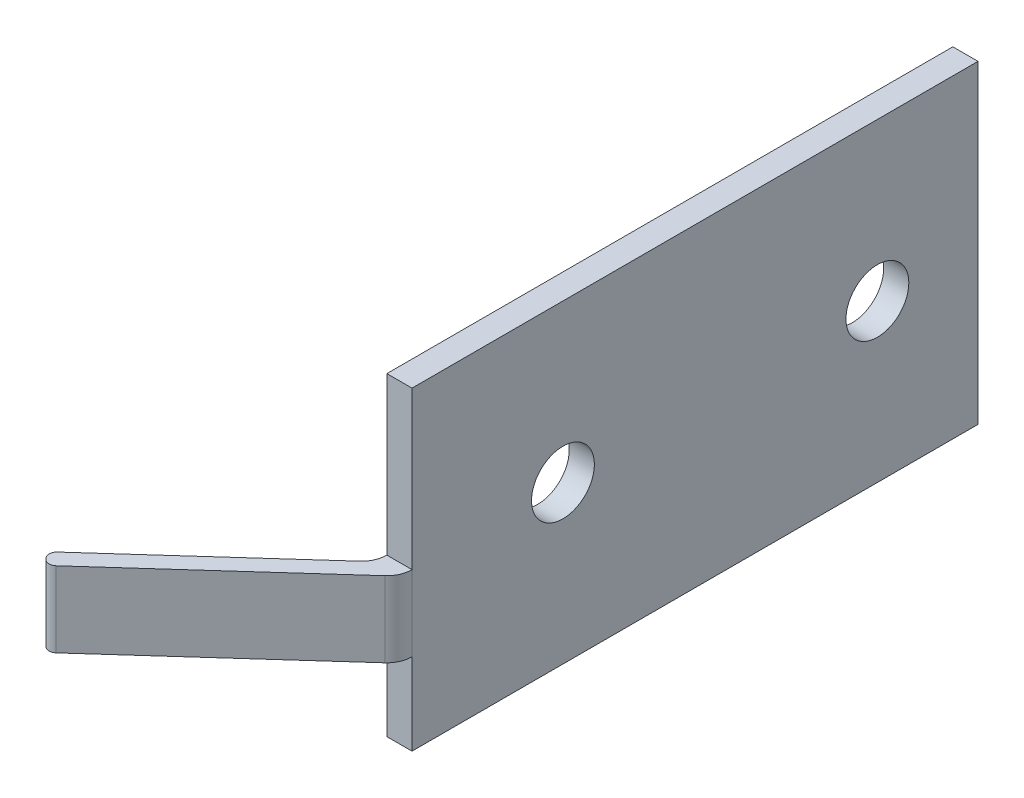
SolidWorks part; units mm, degrees
ref_plane "Front Plane" through (0, 0, 0) normal (0, 0, 1) x (1, 0, 0)
ref_plane "Top Plane" through (0, 0, 0) normal (0, 1, 0) x (1, 0, 0)
ref_plane "Right Plane" through (0, 0, 0) normal (1, 0, 0) x (0, 0, -1)
sketch "Sketch1" plane through (0, 0, 0) normal (0, 1, 0) x (1, 0, 0)
  line L0 (0, 22.5) -> (0, -22.5) construction
  line L1 (-1, -22.5) -> (1, -22.5)
  line L2 (-1, 22.5) -> (1, 22.5)
  line L3 (-1, 22.5) -> (-1, -22.5)
  line L5 (1, 22.5) -> (1, -22.5)
  point P4 (0, 0)
  point P12 (1, 0)
  point P14 (0, 22.5)
  dimension "D1" = 45
  dimension "D2" = 2
extrude "Boss-Extrude1" add sketch "Sketch1" along normal mid plane 25
sketch "Sketch2" plane through (0, 12.5, 0) normal (0, 1, 0) x (1, 0, 0)
  line L6 (1, -22.5) -> (1, -22.5095)
  line L8 (-1, -22.5) -> (1, -22.5) construction
  line L9 (0.3383, -23.9958) -> (-13.417, -36.3811)
  line L10 (-14.2644, -36.3367) -> (-14.3569, -36.234)
  line L11 (-14.3125, -35.3866) -> (-1.6617, -23.9958)
  line L12 (-1, -22.5095) -> (-1, -22.5)
  line L13 (-1, -22.5) -> (1, -22.5)
  arc A0 (-1.6617, -23.9958) -> (-1, -22.5095) centre (-3, -22.5095) ccw
  arc A1 (1, -22.5095) -> (0.3383, -23.9958) centre (-1, -22.5095) cw
  arc A2 (-14.3569, -36.234) -> (-14.3125, -35.3866) centre (-13.911, -35.8325) cw
  arc A3 (-13.417, -36.3811) -> (-14.2644, -36.3367) centre (-13.8185, -35.9352) cw
  point P10 (-1, -23.4)
  point P13 (1, -23.4)
  point P18 (-13.8629, -36.7826)
  dimension "D1" = 20
  dimension "D2" = 0.9
  dimension "D3" = 228
  dimension "D4" = 90
  dimension "D5" = 2
  dimension "D6" = 0.6
extrude "Boss-Extrude2" add sketch "Sketch2" against normal blind 6 from offset 12.5 offset against normal yes
sketch "Sketch3" plane through (1, 0, 0) normal (1, 0, 0) x (0, 0, -1)
  line L0 (22.5095, 0) -> (-22.5095, 0) construction
  line L1 (-22.5, 12.5) -> (-22.5, 0) construction
  circle A0 centre (-10.5, 0) radius 2.5
  circle A1 centre (14.5, 0) radius 2.5
  point P5 (0, 0)
  dimension "D1" = 12
  dimension "D2" = 5
  dimension "D3" = 5
  dimension "D4" = 25
extrude "Cut-Extrude1" cut sketch "Sketch3" against normal mid plane 6
